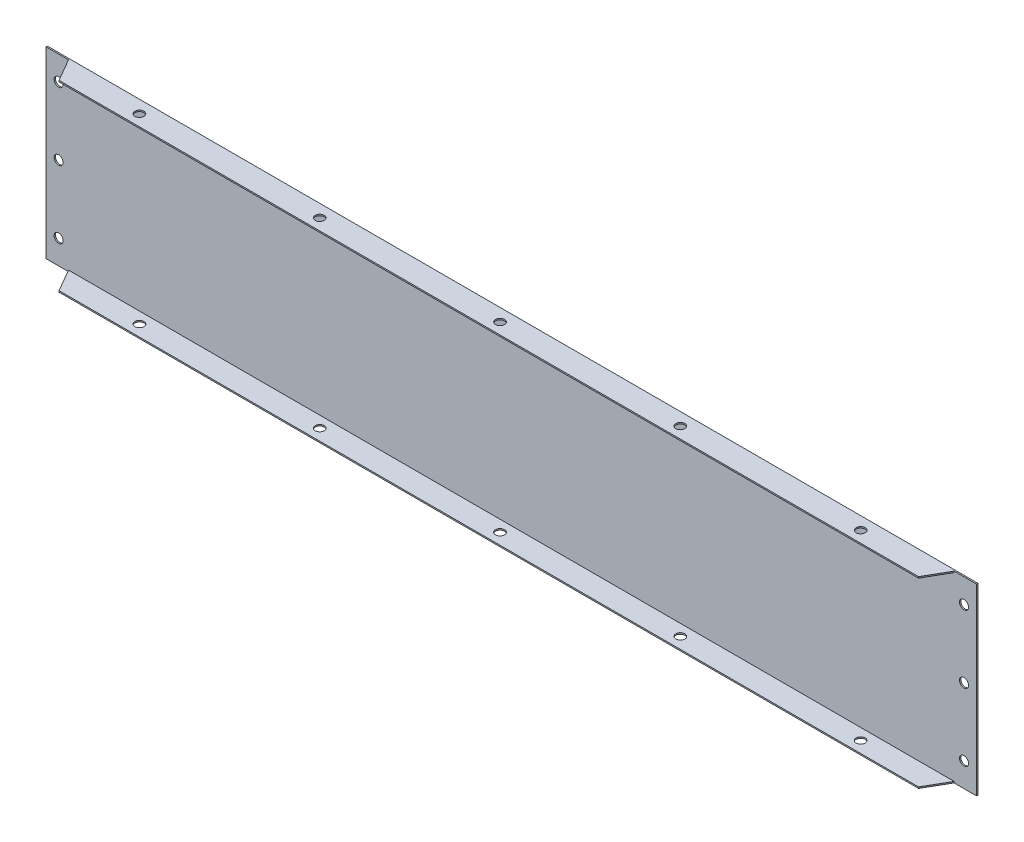
SolidWorks part; units mm, degrees
material "AISI 316 Нержавеющая сталь, лист (SS)"
ref_plane "Спереди" through (0, 0, 0) normal (0, 0, 1) x (1, 0, 0)
ref_plane "Сверху" through (0, 0, 0) normal (0, 1, 0) x (1, 0, 0)
ref_plane "Справа" through (0, 0, 0) normal (1, 0, 0) x (0, 0, -1)
other "Configuration Table"
sketch "Эскиз1" plane through (0, 0, 0) normal (0, 0, 1) x (1, 0, 0)
  line L0 (5.4, 75.5) -> (11.4, 75.5) construction
  line L1 (0, 81.4) -> (482.2, 81.4)
  line L2 (0, 81.4) -> (0, 0)
  line L3 (0, 0) -> (482.2, 0)
  line L4 (482.2, 81.4) -> (482.2, 0)
  line L5 (5.4, 79.5) -> (11.4, 79.5)
  line L6 (5.4, 71.5) -> (11.4, 71.5)
  line L7 (5.4, 5.9) -> (11.4, 5.9) construction
  line L8 (5.4, 9.9) -> (11.4, 9.9)
  line L9 (5.4, 1.9) -> (11.4, 1.9)
  line L10 (470.8, 5.9) -> (476.8, 5.9) construction
  line L11 (470.8, 9.9) -> (476.8, 9.9)
  line L12 (470.8, 1.9) -> (476.8, 1.9)
  line L13 (470.8, 75.5) -> (476.8, 75.5) construction
  line L14 (470.8, 79.5) -> (476.8, 79.5)
  line L15 (470.8, 71.5) -> (476.8, 71.5)
  line L16 (241.1, 81.4) -> (241.1, 0) construction
  line L17 (34.65, 81.4) -> (447.55, 81.4)
  line L18 (34.65, 81.4) -> (34.65, 0)
  line L19 (34.65, 0) -> (447.55, 0)
  line L20 (447.55, 81.4) -> (447.55, 0)
  line L21 (34.65, 40.7) -> (447.55, 40.7) construction
  arc A0 (5.4, 79.5) -> (5.4, 71.5) centre (5.4, 75.5) ccw
  arc A1 (11.4, 71.5) -> (11.4, 79.5) centre (11.4, 75.5) ccw
  arc A2 (5.4, 9.9) -> (5.4, 1.9) centre (5.4, 5.9) ccw
  arc A3 (11.4, 1.9) -> (11.4, 9.9) centre (11.4, 5.9) ccw
  arc A4 (470.8, 9.9) -> (470.8, 1.9) centre (470.8, 5.9) ccw
  arc A5 (476.8, 1.9) -> (476.8, 9.9) centre (476.8, 5.9) ccw
  arc A6 (470.8, 79.5) -> (470.8, 71.5) centre (470.8, 75.5) ccw
  arc A7 (476.8, 71.5) -> (476.8, 79.5) centre (476.8, 75.5) ccw
  circle A8 centre (40.25, 70.7) radius 2
  circle A9 centre (441.95, 70.7) radius 2
  circle A10 centre (441.95, 10.7) radius 2
  circle A11 centre (40.25, 10.7) radius 2
  circle A12 centre (40.25, 40.7) radius 2
  circle A13 centre (441.95, 40.7) radius 2
  point P7 (8.4, 75.5)
  point P15 (8.4, 5.9)
  point P23 (473.8, 5.9)
  point P30 (473.8, 75.5)
  dimension "D14" = 4
  dimension "D19" = 4
  dimension "D20" = 4
  dimension "D1" = 482.2
  dimension "D2" = 81.4
  dimension "D3" = 8
  dimension "D4" = 6
  dimension "D5" = 5.9
  dimension "D6" = 8.4
  dimension "D7" = 8.4
  dimension "D8" = 5.9
  dimension "D9" = 8.4
  dimension "D10" = 5.9
  dimension "D11" = 8.4
  dimension "D12" = 5.9
  dimension "D13" = 412.9
  dimension "D17" = 401.7
  dimension "D18" = 60
  dimension "D15" = 2
  dimension "D16" = 2
extrude "Бобышка-Вытянуть1" add sketch "Эскиз1" along normal blind 0.6 contours L20 L1 L18 L3 A11 A10 A9 A8
sketch "Эскиз2" plane through (0, 81.4, 0) normal (0, 1, 0) x (1, 0, 0)
  line L0 (44.65, -0.6) -> (50.4235, -10.6)
  line L1 (34.65, -0.6) -> (447.55, -0.6) construction
  line L2 (50.4235, -10.6) -> (431.7765, -10.6)
  line L3 (431.7765, -10.6) -> (437.55, -0.6)
  line L4 (437.55, -0.6) -> (44.65, -0.6)
  line L5 (241.1, -10.6) -> (241.1, -0.6) construction
  line L6 (401.1, -5.6) -> (321.1, -5.6) construction
  circle A0 centre (401.1, -5.6) radius 2
  circle A1 centre (321.1, -5.6) radius 2
  circle A2 centre (241.1, -5.6) radius 2
  circle A3 centre (161.1, -5.6) radius 2
  circle A4 centre (81.1, -5.6) radius 2
  dimension "D6" = 4
  dimension "D1" = 60
  dimension "D2" = 60
  dimension "D3" = 10
  dimension "D4" = 10
  dimension "D5" = 10
  dimension "D7" = 80
extrude "Бобышка-Вытянуть2" add sketch "Эскиз2" against normal blind 0.6
sketch "Эскиз3" plane through (0, 0, 0) normal (0, -1, 0) x (1, 0, 0)
  line L4 (44.65, 0.6) -> (437.55, 0.6)
  line L5 (437.55, 0.6) -> (431.7765, 10.6)
  line L6 (431.7765, 10.6) -> (50.4235, 10.6)
  line L7 (50.4235, 10.6) -> (44.65, 0.6)
  line L8 (44.65, 0.6) -> (437.55, 0.6)
  line L9 (437.55, 0.6) -> (431.7765, 10.6)
  line L10 (431.7765, 10.6) -> (50.4235, 10.6)
  line L11 (50.4235, 10.6) -> (44.65, 0.6)
  circle A0 centre (401.1, 5.6) radius 2 construction
  circle A1 centre (321.1, 5.6) radius 2 construction
  circle A2 centre (241.1, 5.6) radius 2 construction
  circle A3 centre (161.1, 5.6) radius 2 construction
  circle A4 centre (81.1, 5.6) radius 2 construction
  circle A5 centre (401.1, 5.6) radius 2
  circle A6 centre (321.1, 5.6) radius 2
  circle A7 centre (241.1, 5.6) radius 2
  circle A8 centre (161.1, 5.6) radius 2
  circle A9 centre (81.1, 5.6) radius 2
  dimension "D1" = 0
extrude "Бобышка-Вытянуть3" add sketch "Эскиз3" against normal blind 0.6
